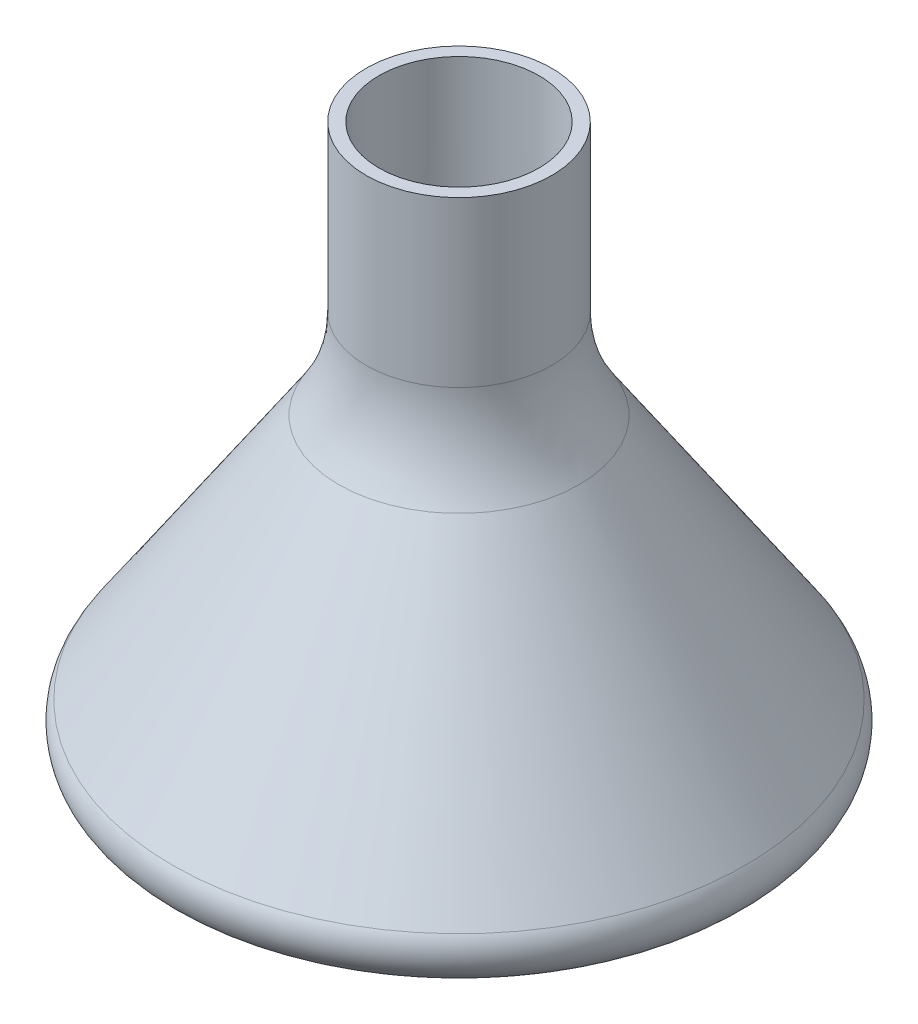
SolidWorks part; units mm, degrees
ref_plane "Plan de face" through (0, 0, 0) normal (0, 0, 1) x (1, 0, 0)
ref_plane "Plan de dessus" through (0, 0, 0) normal (0, 1, 0) x (1, 0, 0)
ref_plane "Plan de droite" through (0, 0, 0) normal (1, 0, 0) x (0, 0, -1)
sketch "Esquisse2" plane through (0, 0, 0) normal (1, 0, 0) x (0, 0, -1)
  line L0 (8.7, 31.567) -> (26.8435, 4.678)
  line L1 (24.3567, 0) -> (0, 0)
  line L2 (7.5, 31.2) -> (25.8488, 4.0068)
  line L3 (24.3567, 1.2) -> (0, 1.2)
  line L4 (-9.4524, 56.3238) -> (25.8488, 4.0068) construction
  line L5 (-8.4577, 56.995) -> (26.8435, 4.678) construction
  line L6 (0, 1.2) -> (0, 0)
  line L10 (8.7, 31.567) -> (8.7, 51.567)
  line L11 (8.7, 51.567) -> (7.5, 51.567)
  line L12 (7.5, 31.2) -> (7.5, 51.567)
  arc A0 (26.8435, 4.678) -> (24.3567, 0) centre (24.3567, 3) cw
  arc A1 (25.8488, 4.0068) -> (24.3567, 1.2) centre (24.3567, 3) cw
  point P4 (30, 0)
  dimension "D5" = 3
  dimension "D1" = 30
  dimension "D3" = 7.5
  dimension "D4" = 30
  dimension "D2" = 1.2
  dimension "D6" = 20
  dimension "D7" = 1.2
revolve "Révolution1" add sketch "Esquisse2" angle 360 about L6
sketch "Esquisse3" plane through (0, 0, 0) normal (0, -1, 0) x (1, 0, 0)
  line L0 (-29.6985, 0) -> (-39.598, 0)
  line L1 (-39.598, 0) -> (-34.6482, -4.9497)
  circle A277 centre (-39.598, 0) radius 1.25 construction
  circle A279 centre (-34.6482, 4.9497) radius 1.25 construction
  circle A280 centre (-29.6985, 9.8995) radius 1.25 construction
  circle A281 centre (-24.7487, 14.8492) radius 1.25 construction
  circle A282 centre (-19.799, 19.799) radius 1.25 construction
  circle A283 centre (-14.8492, 24.7487) radius 1.25 construction
  circle A284 centre (-9.8995, 29.6985) radius 1.25 construction
  circle A285 centre (-4.9497, 34.6482) radius 1.25 construction
  circle A286 centre (-29.6985, 0) radius 1.25 construction
  circle A287 centre (-24.7487, 4.9497) radius 1.25 construction
  circle A288 centre (-19.799, 9.8995) radius 1.25
  circle A289 centre (-14.8492, 14.8492) radius 1.25
  circle A290 centre (-9.8995, 19.799) radius 1.25
  circle A291 centre (-4.9497, 24.7487) radius 1.25 construction
  circle A292 centre (0, 29.6985) radius 1.25 construction
  circle A293 centre (-24.7487, -4.9497) radius 1.25 construction
  circle A294 centre (-19.799, 0) radius 1.25
  circle A295 centre (-14.8492, 4.9497) radius 1.25
  circle A296 centre (-9.8995, 9.8995) radius 1.25
  circle A297 centre (-4.9497, 14.8492) radius 1.25
  circle A298 centre (0, 19.799) radius 1.25
  circle A299 centre (4.9497, 24.7487) radius 1.25 construction
  circle A300 centre (-19.799, -9.8995) radius 1.25
  circle A301 centre (-14.8492, -4.9497) radius 1.25
  circle A302 centre (-9.8995, 0) radius 1.25
  circle A303 centre (-4.9497, 4.9497) radius 1.25
  circle A304 centre (0, 9.8995) radius 1.25
  circle A305 centre (4.9497, 14.8492) radius 1.25
  circle A306 centre (9.8995, 19.799) radius 1.25
  circle A307 centre (-14.8492, -14.8492) radius 1.25
  circle A308 centre (-9.8995, -9.8995) radius 1.25
  circle A309 centre (-4.9497, -4.9497) radius 1.25
  circle A310 centre (0, 0) radius 1.25
  circle A311 centre (4.9497, 4.9497) radius 1.25
  circle A312 centre (9.8995, 9.8995) radius 1.25
  circle A313 centre (14.8492, 14.8492) radius 1.25
  circle A314 centre (-9.8995, -19.799) radius 1.25
  circle A315 centre (-4.9497, -14.8492) radius 1.25
  circle A316 centre (0, -9.8995) radius 1.25
  circle A317 centre (4.9497, -4.9497) radius 1.25
  circle A318 centre (9.8995, 0) radius 1.25
  circle A319 centre (14.8492, 4.9497) radius 1.25
  circle A320 centre (19.799, 9.8995) radius 1.25
  circle A321 centre (-4.9497, -24.7487) radius 1.25 construction
  circle A322 centre (0, -19.799) radius 1.25
  circle A323 centre (4.9497, -14.8492) radius 1.25
  circle A324 centre (9.8995, -9.8995) radius 1.25
  circle A325 centre (14.8492, -4.9497) radius 1.25
  circle A326 centre (19.799, 0) radius 1.25
  circle A327 centre (24.7487, 4.9497) radius 1.25 construction
  circle A328 centre (0, -29.6985) radius 1.25 construction
  circle A329 centre (4.9497, -24.7487) radius 1.25 construction
  circle A330 centre (9.8995, -19.799) radius 1.25
  circle A331 centre (14.8492, -14.8492) radius 1.25
  circle A332 centre (19.799, -9.8995) radius 1.25
  circle A333 centre (24.7487, -4.9497) radius 1.25 construction
  circle A334 centre (29.6985, 0) radius 1.25 construction
  circle A335 centre (-34.6482, -4.9497) radius 1.25 construction
  circle A336 centre (-29.6985, -9.8995) radius 1.25 construction
  circle A337 centre (-24.7487, -14.8492) radius 1.25 construction
  circle A338 centre (-19.799, -19.799) radius 1.25 construction
  circle A339 centre (-14.8492, -24.7487) radius 1.25 construction
  circle A340 centre (-9.8995, -29.6985) radius 1.25 construction
  circle A341 centre (-4.9497, -34.6482) radius 1.25 construction
  circle A342 centre (0, 39.598) radius 1.25 construction
  circle A343 centre (4.9497, 34.6482) radius 1.25 construction
  circle A344 centre (9.8995, 29.6985) radius 1.25 construction
  circle A345 centre (14.8492, 24.7487) radius 1.25 construction
  circle A346 centre (19.799, 19.799) radius 1.25 construction
  circle A347 centre (24.7487, 14.8492) radius 1.25 construction
  circle A348 centre (29.6985, 9.8995) radius 1.25 construction
  circle A349 centre (34.6482, 4.9497) radius 1.25 construction
  circle A350 centre (0, -39.598) radius 1.25 construction
  circle A351 centre (4.9497, -34.6482) radius 1.25 construction
  circle A352 centre (9.8995, -29.6985) radius 1.25 construction
  circle A353 centre (14.8492, -24.7487) radius 1.25 construction
  circle A354 centre (19.799, -19.799) radius 1.25 construction
  circle A355 centre (24.7487, -14.8492) radius 1.25 construction
  circle A356 centre (29.6985, -9.8995) radius 1.25 construction
  circle A357 centre (34.6482, -4.9497) radius 1.25 construction
  circle A358 centre (39.598, 0) radius 1.25 construction
  point P162 (0, 0)
  point P163 (0, 0)
  point P164 (0, 0)
  point P165 (0, 0)
  point P166 (0, 0)
  dimension "D1" = 2.5
  dimension "D4" = 7
  dimension "D5" = 7
  dimension "D2" = 9
  dimension "D3" = 9
extrude "Enlèv. mat.-Extru.2" cut sketch "Esquisse3" against normal up to surface (1.2 mm away) contours A302 | A309 | A310 | A311 | A306 | A305 | A313 | A320 | A319 | A326 | A325 | A294 | A295 | A288 | A289 | A290 | A298 | A297 | A296 | A303 | A304 | A312 | A318 | A317 | A316 | A308 | A301 | A300 | A307 | A314 | A315 | A322 | A323 | A324 | A330 | A331 | A332 up to face at (0, 1.2, 24.3567)
fillet "Congé1" radius 15 2 edges at (0, 31.567, 8.7) (0, 31.2, 7.5)
